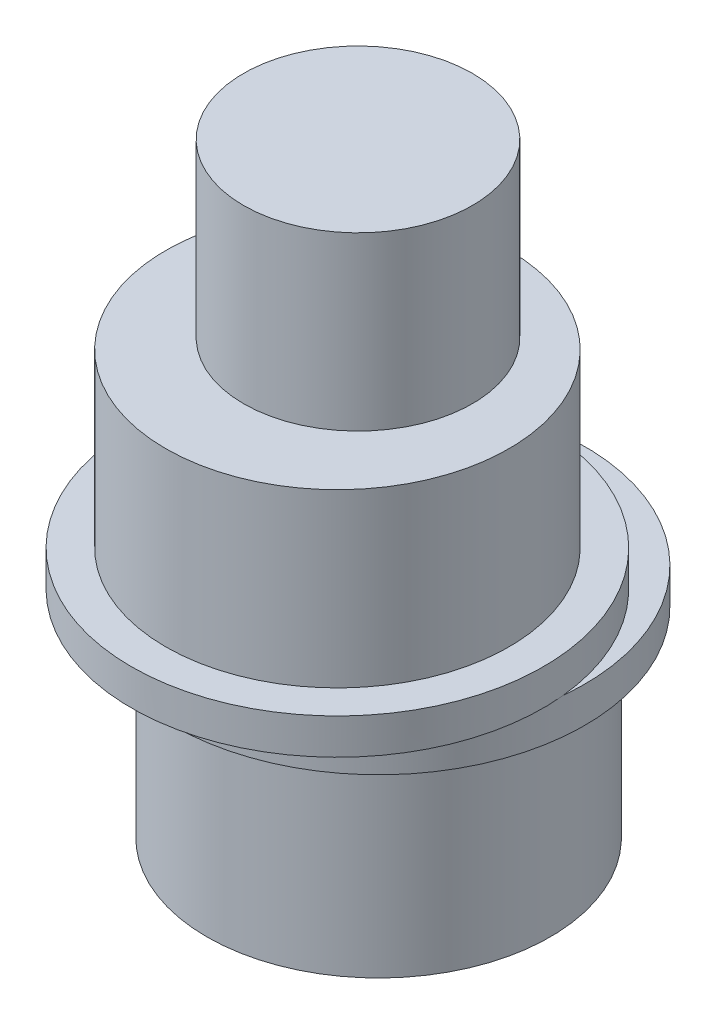
SolidWorks part; units mm, degrees
ref_plane "Front Plane" through (0, 0, 0) normal (0, 0, 1) x (1, 0, 0)
ref_plane "Top Plane" through (0, 0, 0) normal (0, 1, 0) x (1, 0, 0)
ref_plane "Right Plane" through (0, 0, 0) normal (1, 0, 0) x (0, 0, -1)
sketch "Sketch1" plane through (0, 0, 0) normal (0, 1, 0) x (1, 0, 0)
  circle A0 centre (0, 0.72) radius 6
  dimension "D1" = 12
  dimension "D2" = 0.72
extrude "Boss-Extrude1" add sketch "Sketch1" along normal blind 7
sketch "Sketch2" plane through (0, 7, 0) normal (0, 1, 0) x (1, 0, 0)
  circle A0 centre (0, 0.72) radius 7.2
  dimension "D1" = 14.4
extrude "Boss-Extrude2" add sketch "Sketch2" along normal blind 1.25
sketch "Sketch3" plane through (0, 8.25, 0) normal (0, 1, 0) x (1, 0, 0)
  circle A0 centre (0, -0.72) radius 7.2
  dimension "D1" = 14.4
  dimension "D2" = 0.72
extrude "Boss-Extrude3" add sketch "Sketch3" along normal blind 1.25
sketch "Sketch4" plane through (0, 9.5, 0) normal (0, 1, 0) x (1, 0, 0)
  circle A0 centre (0, -0.72) radius 6
  dimension "D1" = 12
  dimension "D2" = 0.72
extrude "Boss-Extrude4" add sketch "Sketch4" along normal blind 6
sketch "Sketch5" plane through (0, 0, 0) normal (0, -1, 0) x (1, 0, 0)
  line L0 (0, 0) -> (0, 2) construction
  line L1 (1.5, 2) -> (-1.5, 2)
  arc A0 (-1.5, 2) -> (1.5, 2) centre (0, 0) ccw
  point P7 (0, 2)
  dimension "D1" = 5
  dimension "D2" = 2
extrude "Cut-Extrude2" cut sketch "Sketch5" against normal blind 11 and the other way through all
sketch "Sketch6" plane through (0, 15.5, 0) normal (0, 1, 0) x (1, 0, 0)
  circle A0 centre (0, 0) radius 4
  dimension "D1" = 8
extrude "Boss-Extrude5" add sketch "Sketch6" along normal blind 6
sketch "Sketch7" plane through (0, 15.5, 0) normal (0, 1, 0) x (1, 0, 0)
  line L0 (0, 5.28) -> (0, -6.72) construction
  circle A0 centre (0, -0.72) radius 6 construction
  circle A1 centre (0, -0.72) radius 6 construction
